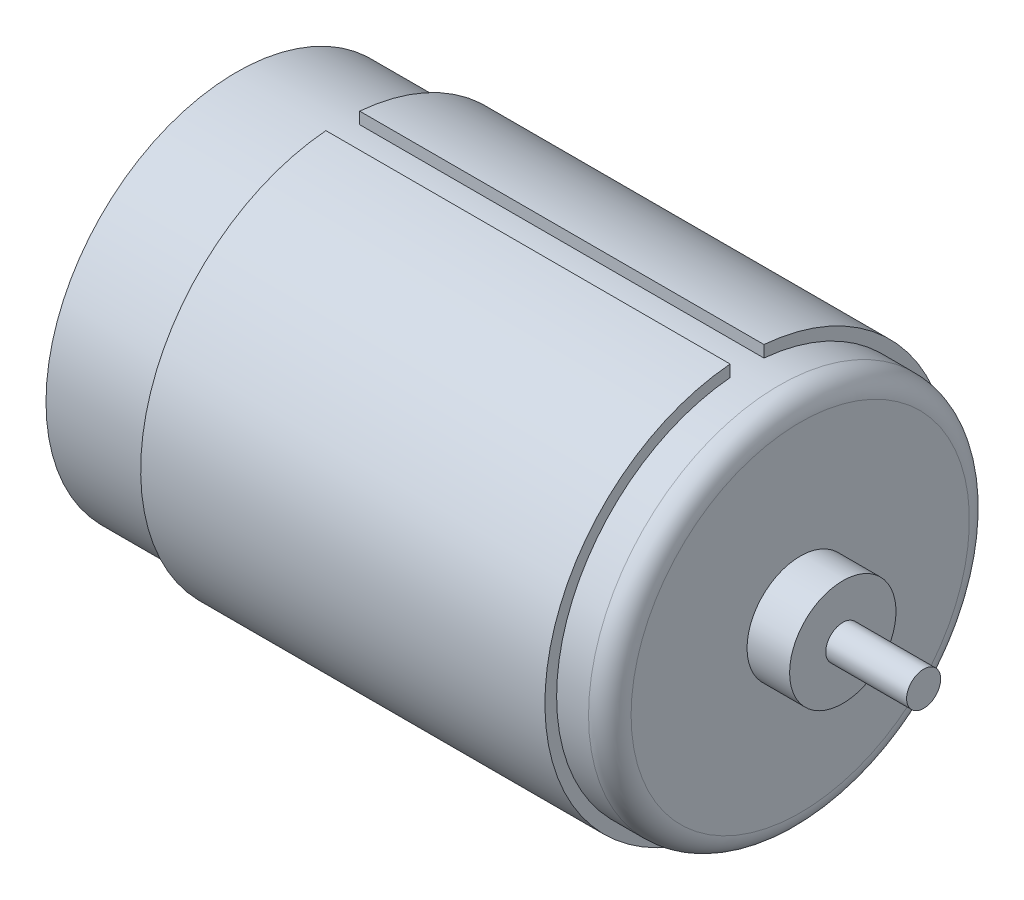
SolidWorks part; units mm, degrees
material "Plain Carbon Steel"
ref_plane "Front Plane" through (0, 0, 0) normal (0, 0, 1) x (1, 0, 0)
ref_plane "Top Plane" through (0, 0, 0) normal (0, 1, 0) x (1, 0, 0)
ref_plane "Right Plane" through (0, 0, 0) normal (1, 0, 0) x (0, 0, -1)
sketch "Sketch3" plane through (0, 0, 0) normal (0, 0, 1) x (1, 0, 0)
  line L0 (0, 0) -> (64.6, 0) construction
  line L1 (0, 0) -> (0, 17.9)
  line L2 (0, 17.9) -> (10, 17.9)
  line L3 (10, 17.9) -> (10, 19)
  line L4 (10, 19) -> (48, 19)
  line L5 (48, 19) -> (48, 17.9)
  line L6 (48, 17.9) -> (51, 17.9)
  line L7 (53, 15.9) -> (53, 5)
  line L8 (53, 5) -> (57, 5)
  line L9 (57, 5) -> (57, 1.6)
  line L10 (57, 1.6) -> (64.6, 1.6)
  line L11 (64.6, 1.6) -> (64.6, 0)
  line L12 (0, 0) -> (3.512, 0)
  line L13 (49.6755, 14.1006) -> (49.6755, 0)
  line L14 (3.512, 14.1006) -> (49.6755, 14.1006)
  line L15 (3.512, 14.1006) -> (3.512, 0)
  line L16 (49.6755, 0) -> (64.6, 0)
  arc A0 (51, 17.9) -> (53, 15.9) centre (51, 15.9) cw
  point P15 (53, 17.9)
  dimension "D10" = 2
  dimension "D1" = 7.6
  dimension "D2" = 3.2
  dimension "D3" = 57
  dimension "D4" = 35.8
  dimension "D5" = 38
  dimension "D6" = 4
  dimension "D7" = 10
  dimension "D8" = 5
  dimension "D9" = 10
revolve "Revolve1" add sketch "Sketch3" angle 360 about L0
sketch "Sketch4" plane through (10, 0, 0) normal (-1, 0, 0) x (0, 0, 1)
  line L0 (0, 17.9) -> (0, 0) construction
  line L1 (1.5875, 18.9336) -> (1.5875, 17.8295)
  line L2 (-1.5875, 18.9336) -> (-1.5875, 17.8295)
  arc A0 (-1.5875, 17.8295) -> (1.5875, 17.8295) centre (0, 0) cw
  circle A1 centre (0, 0) radius 17.9 construction
  arc A2 (-1.5875, 18.9336) -> (1.5875, 18.9336) centre (0, 0) cw
  circle A3 centre (0, 0) radius 19 construction
  dimension "D1" = 3.175
extrude "Cut-Extrude1" cut sketch "Sketch4" against normal up to next
